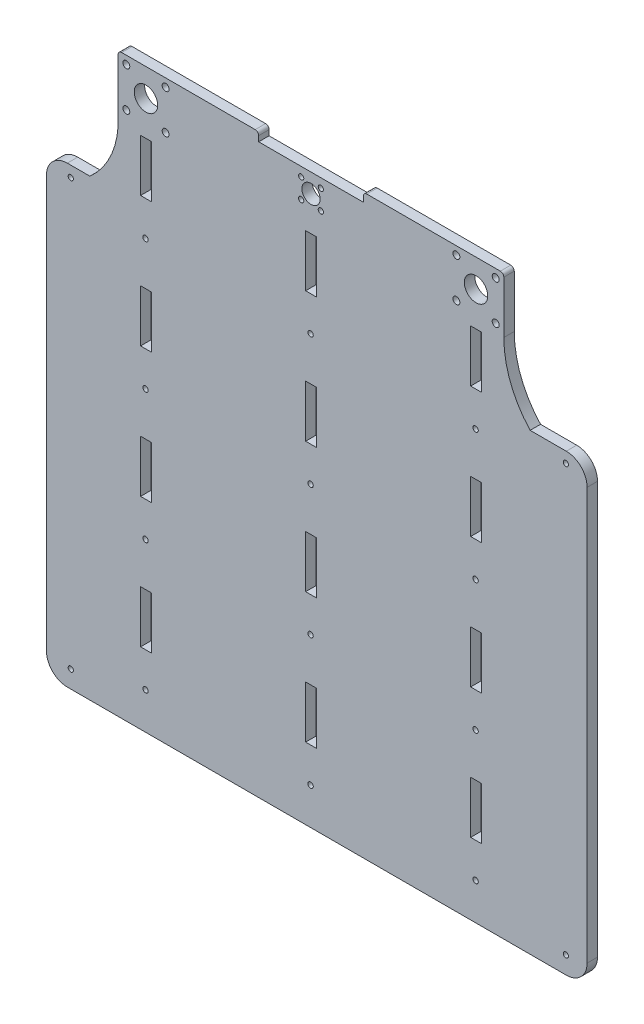
SolidWorks part; units mm, degrees
ref_plane "Alzado" through (0, 0, 0) normal (0, 0, 1) x (1, 0, 0)
ref_plane "Planta" through (0, 0, 0) normal (0, 1, 0) x (1, 0, 0)
ref_plane "Vista lateral" through (0, 0, 0) normal (1, 0, 0) x (0, 0, -1)
sketch "Croquis1" plane through (0, 0, 0) normal (0, 0, 1) x (1, 0, 0)
  line L0 (32.1154, 16) -> (87.6356, 16)
  line L1 (-109, 16) -> (-87.6356, 16)
  line L2 (-111, 14) -> (-111, -16.0875)
  line L3 (-135.2776, -316) -> (-119.3643, -316)
  line L4 (-87.6356, 16) -> (-44.6644, 16)
  line L5 (30.1154, 14) -> (30.1154, 10.91)
  line L6 (0, 0) -> (0, 78.8056) construction
  line L7 (30.1154, 10.91) -> (-30.1154, 10.91)
  line L8 (-111, 0) -> (-111, -16)
  line L9 (-111, -16) -> (-111, 16)
  line L10 (-44.6644, 16) -> (-32.1154, 16)
  line L11 (-119.3643, -316) -> (119.3644, -316)
  line L12 (111, 14) -> (111, -16.0875)
  line L13 (109, 16) -> (87.6356, 16)
  line L14 (-30.1154, 14) -> (-30.1154, 10.91)
  line L15 (-8.3, -8.3) -> (8.3, 8.3) construction
  line L16 (-127.2776, -54.7893) -> (126.134, -54.7893) construction
  line L17 (-96, -316) -> (-44.6644, -316)
  line L18 (119.3644, -316) -> (130.2951, -316)
  line L19 (-8.3, 8.3) -> (8.3, -8.3) construction
  line L20 (-127.2776, -54.7893) -> (-135.2776, -54.7893)
  line L21 (-111, 16) -> (-79, -16) construction
  line L22 (-111, -16) -> (-79, 16) construction
  line L23 (-135.2776, -54.7893) -> (-140.2776, -54.7893)
  line L24 (-138.2776, -61) -> (-136.7776, -61) construction
  line L25 (-95, 0) -> (-95, -306) construction
  line L26 (-135.2776, -316) -> (-140.2776, -316)
  line L27 (-152.2776, -66.7893) -> (-152.2776, -304)
  line L28 (0, 0) -> (0, -306) construction
  line L29 (130.2951, -316) -> (146.9429, -316)
  line L30 (158.9429, -70.8585) -> (158.9429, -304)
  line L31 (145.2224, -61) -> (146.7224, -61) construction
  line L32 (126.134, -54.7893) -> (146.9429, -54.7893)
  line L33 (-111, -16.0875) -> (-79, -16) construction
  line L34 (-95, -49.8402) -> (-95.2397, -69.8402) construction
  line L35 (158.9429, -66.7893) -> (158.9429, -70.8585)
  line L36 (-98.1, -94.8402) -> (-91.9, -94.8402)
  line L37 (-98.1, -19.8402) -> (-91.9, -19.8402)
  line L38 (-98.1, -19.8402) -> (-98.1, -49.8402)
  line L39 (-98.1, -49.8402) -> (-91.9, -49.8402)
  line L40 (-91.9, -19.8402) -> (-91.9, -49.8402)
  line L41 (-98.1, -19.8402) -> (-91.9, -49.8402) construction
  line L42 (-98.1, -49.8402) -> (-91.9, -19.8402) construction
  line L43 (-98.1, -94.8402) -> (-98.1, -124.8402)
  line L44 (-98.1, -124.8402) -> (-91.9, -124.8402)
  line L45 (-91.9, -94.8402) -> (-91.9, -124.8402)
  line L46 (-95, -124.8402) -> (-95.2397, -144.8402) construction
  line L47 (-98.1, -94.8402) -> (-91.9, -124.8402) construction
  line L48 (-98.1, -124.8402) -> (-91.9, -94.8402) construction
  line L49 (-98.1, -169.8402) -> (-91.9, -169.8402)
  line L50 (-98.1, -169.8402) -> (-98.1, -199.8402)
  line L51 (-98.1, -199.8402) -> (-91.9, -199.8402)
  line L52 (-91.9, -169.8402) -> (-91.9, -199.8402)
  line L53 (-95, -199.8402) -> (-95.2397, -219.8402) construction
  line L54 (-98.1, -169.8402) -> (-91.9, -199.8402) construction
  line L55 (-98.1, -199.8402) -> (-91.9, -169.8402) construction
  line L56 (-98.1, -244.8402) -> (-91.9, -244.8402)
  line L57 (-98.1, -244.8402) -> (-98.1, -274.8402)
  line L58 (-98.1, -274.8402) -> (-91.9, -274.8402)
  line L59 (-91.9, -244.8402) -> (-91.9, -274.8402)
  line L60 (-95, -274.8402) -> (-95.2397, -294.8402) construction
  line L61 (-98.1, -244.8402) -> (-91.9, -274.8402) construction
  line L62 (-98.1, -274.8402) -> (-91.9, -244.8402) construction
  line L63 (0, -49.8402) -> (-0.2397, -69.8402) construction
  line L64 (-3.1, -94.8402) -> (3.1, -94.8402)
  line L65 (-3.1, -19.8402) -> (3.1, -19.8402)
  line L66 (-3.1, -19.8402) -> (-3.1, -49.8402)
  line L67 (-3.1, -49.8402) -> (3.1, -49.8402)
  line L68 (3.1, -19.8402) -> (3.1, -49.8402)
  line L69 (-3.1, -19.8402) -> (3.1, -49.8402) construction
  line L70 (-3.1, -49.8402) -> (3.1, -19.8402) construction
  line L71 (-3.1, -94.8402) -> (-3.1, -124.8402)
  line L72 (-3.1, -124.8402) -> (3.1, -124.8402)
  line L73 (3.1, -94.8402) -> (3.1, -124.8402)
  line L74 (0, -124.8402) -> (-0.2397, -144.8402) construction
  line L75 (-3.1, -94.8402) -> (3.1, -124.8402) construction
  line L76 (-3.1, -124.8402) -> (3.1, -94.8402) construction
  line L77 (-3.1, -169.8402) -> (3.1, -169.8402)
  line L78 (-3.1, -169.8402) -> (-3.1, -199.8402)
  line L79 (-3.1, -199.8402) -> (3.1, -199.8402)
  line L80 (3.1, -169.8402) -> (3.1, -199.8402)
  line L81 (0, -199.8402) -> (-0.2397, -219.8402) construction
  line L82 (-3.1, -169.8402) -> (3.1, -199.8402) construction
  line L83 (-3.1, -199.8402) -> (3.1, -169.8402) construction
  line L84 (-3.1, -244.8402) -> (3.1, -244.8402)
  line L85 (-3.1, -244.8402) -> (-3.1, -274.8402)
  line L86 (-3.1, -274.8402) -> (3.1, -274.8402)
  line L87 (3.1, -244.8402) -> (3.1, -274.8402)
  line L88 (0, -274.8402) -> (-0.2397, -294.8402) construction
  line L89 (-3.1, -244.8402) -> (3.1, -274.8402) construction
  line L90 (-3.1, -274.8402) -> (3.1, -244.8402) construction
  line L91 (-91.9, -19.8402) -> (106.3137, -19.8402) construction
  line L92 (106.3137, -19.8402) -> (95, 0) construction
  line L93 (95, 0) -> (95, -119.0864) construction
  line L94 (95, -49.8402) -> (94.7603, -69.8402) construction
  line L95 (91.9, -94.8402) -> (98.1, -94.8402)
  line L96 (91.9, -19.8402) -> (98.1, -19.8402)
  line L97 (91.9, -19.8402) -> (91.9, -49.8402)
  line L98 (91.9, -49.8402) -> (98.1, -49.8402)
  line L99 (98.1, -19.8402) -> (98.1, -49.8402)
  line L100 (91.9, -19.8402) -> (98.1, -49.8402) construction
  line L101 (91.9, -49.8402) -> (98.1, -19.8402) construction
  line L102 (91.9, -94.8402) -> (91.9, -124.8402)
  line L103 (91.9, -124.8402) -> (98.1, -124.8402)
  line L104 (98.1, -94.8402) -> (98.1, -124.8402)
  line L105 (95, -124.8402) -> (94.7603, -144.8402) construction
  line L106 (91.9, -94.8402) -> (98.1, -124.8402) construction
  line L107 (91.9, -124.8402) -> (98.1, -94.8402) construction
  line L108 (91.9, -169.8402) -> (98.1, -169.8402)
  line L109 (91.9, -169.8402) -> (91.9, -199.8402)
  line L110 (91.9, -199.8402) -> (98.1, -199.8402)
  line L111 (98.1, -169.8402) -> (98.1, -199.8402)
  line L112 (95, -199.8402) -> (94.7603, -219.8402) construction
  line L113 (91.9, -169.8402) -> (98.1, -199.8402) construction
  line L114 (91.9, -199.8402) -> (98.1, -169.8402) construction
  line L115 (91.9, -244.8402) -> (98.1, -244.8402)
  line L116 (91.9, -244.8402) -> (91.9, -274.8402)
  line L117 (91.9, -274.8402) -> (98.1, -274.8402)
  line L118 (98.1, -244.8402) -> (98.1, -274.8402)
  line L119 (95, -274.8402) -> (94.7603, -294.8402) construction
  line L120 (91.9, -244.8402) -> (98.1, -274.8402) construction
  line L121 (91.9, -274.8402) -> (98.1, -244.8402) construction
  circle A0 centre (0, 0) radius 5.25
  circle A1 centre (-95, 0) radius 6.75
  circle A2 centre (95, 0) radius 6.75
  circle A3 centre (146.7224, -61) radius 1.5
  circle A4 centre (-83.6863, 11.3137) radius 2
  circle A5 centre (-106.3137, 11.3137) radius 2
  circle A6 centre (-83.6863, -11.3137) radius 2
  circle A7 centre (-106.3137, -11.3137) radius 2
  circle A8 centre (106.3137, -11.3137) radius 2
  circle A9 centre (83.6863, -11.3137) radius 2
  circle A10 centre (83.6863, 11.3137) radius 2
  arc A11 (-111, -16.0875) -> (-127.2776, -54.7893) centre (-158.9474, -18.6953) cw
  arc A12 (111, -16.0875) -> (126.134, -54.7893) centre (168.0523, -16.0875) ccw
  arc A13 (-140.2776, -316) -> (-152.2776, -304) centre (-140.2776, -304) cw
  arc A14 (158.9429, -304) -> (146.9429, -316) centre (146.9429, -304) cw
  arc A15 (158.9429, -66.7893) -> (146.9429, -54.7893) centre (146.9429, -66.7893) ccw
  circle A16 centre (5.6569, 5.6569) radius 1.5
  circle A17 centre (-5.6569, 5.6569) radius 1.5
  circle A18 centre (-5.6569, -5.6569) radius 1.5
  circle A19 centre (5.6569, -5.6569) radius 1.5
  arc A20 (-140.2776, -54.7893) -> (-152.2776, -66.7893) centre (-140.2776, -66.7893) ccw
  circle A21 centre (146.7224, -306) radius 1.5
  circle A22 centre (-138.2776, -306) radius 1.5
  circle A23 centre (-138.2776, -61) radius 1.5
  circle A24 centre (-95.2397, -69.8402) radius 1.55
  circle A25 centre (-95.2397, -144.8402) radius 1.55
  circle A26 centre (-95.2397, -219.8402) radius 1.55
  circle A27 centre (-95.2397, -294.8402) radius 1.55
  circle A28 centre (-0.2397, -69.8402) radius 1.55
  arc A29 (109, 16) -> (111, 14) centre (109, 14) cw
  arc A30 (-111, 14) -> (-109, 16) centre (-109, 14) cw
  circle A31 centre (-0.2397, -144.8402) radius 1.55
  circle A32 centre (-0.2397, -219.8402) radius 1.55
  circle A33 centre (-0.2397, -294.8402) radius 1.55
  circle A34 centre (94.7603, -69.8402) radius 1.55
  arc A35 (-32.1154, 16) -> (-30.1154, 14) centre (-32.1154, 14) cw
  circle A36 centre (94.7603, -144.8402) radius 1.55
  circle A37 centre (106.3137, 11.3137) radius 2
  arc A38 (30.1154, 14) -> (32.1154, 16) centre (32.1154, 14) cw
  circle A39 centre (94.7603, -219.8402) radius 1.55
  circle A40 centre (94.7603, -294.8402) radius 1.55
  point P57 (-95, -34.8402)
  point P71 (0, 16)
  point P81 (-95, -109.8402)
  point P90 (-95, -184.8402)
  point P98 (111, 16)
  point P101 (-111, 16)
  point P106 (30.1154, 16)
  point P108 (-147.2776, -54.7893)
  point P124 (-95, -259.8402)
  point P132 (0, -34.8402)
  point P140 (0, -109.8402)
  point P148 (0, -184.8402)
  point P156 (0, -259.8402)
  point P164 (95, -34.8402)
  point P174 (95, -109.8402)
  point P182 (95, -184.8402)
  point P190 (95, -259.8402)
  dimension "D3" = 285
  dimension "D4" = 12
  dimension "D5" = 10.5
  dimension "D6" = 14
  dimension "D7" = 285
  dimension "D8" = 13.5
  dimension "D9" = 245
  dimension "D10" = 4
  dimension "D11" = 222
  dimension "D12" = 16
  dimension "D13" = 16
  dimension "D16" = 190
  dimension "D2" = 13.5
  dimension "D18" = 14
  dimension "D21" = 4
  dimension "D19" = 4
  dimension "D20" = 4
  dimension "D22" = 2
  dimension "D24" = 12
  dimension "D25" = 12
  dimension "D14" = 10.91
  dimension "D15" = 11.3137
  dimension "D17" = 95
  dimension "D23" = 20
  dimension "D26" = 11.3137
  dimension "D27" = 11.3137
  dimension "D28" = 11.3137
  dimension "D29" = 16
  dimension "D30" = 16
extrude "Saliente-Extruir1" add sketch "Croquis1" along normal blind 6
